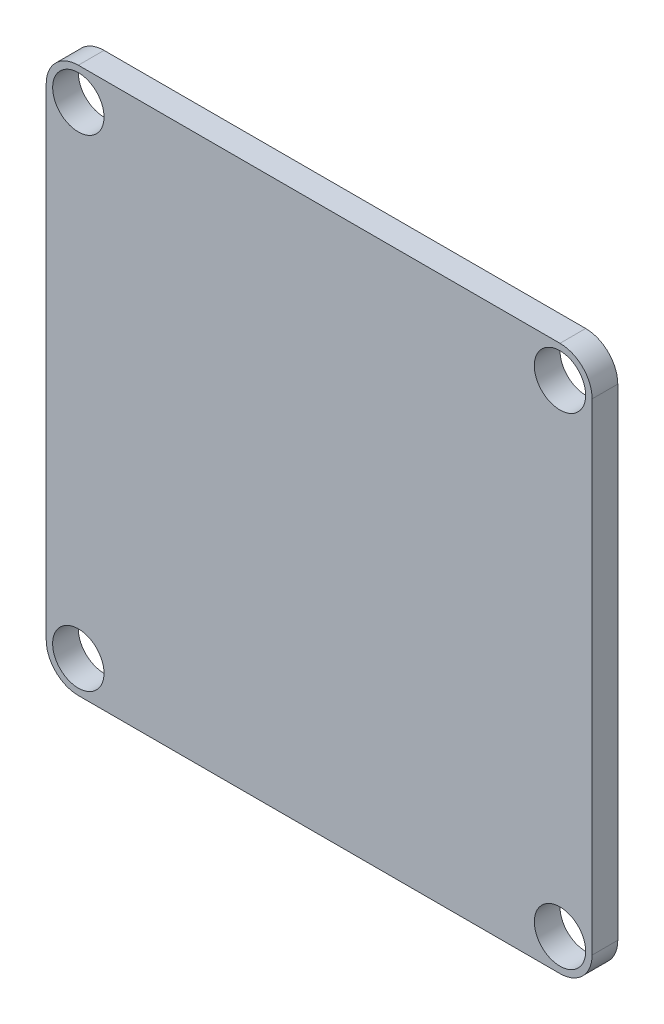
SolidWorks part; units mm, degrees
ref_plane "Front Plane" through (0, 0, 0) normal (0, 0, 1) x (1, 0, 0)
ref_plane "Top Plane" through (0, 0, 0) normal (0, 1, 0) x (1, 0, 0)
ref_plane "Right Plane" through (0, 0, 0) normal (1, 0, 0) x (0, 0, -1)
sketch "Sketch1" plane through (0, 0, 0) normal (0, 0, 1) x (1, 0, 0)
  line L0 (1.7643, 13.6116) -> (1.7643, -20.3884) construction
  line L1 (-13.2357, 13.6116) -> (16.7643, 13.6116)
  line L2 (-15.2357, 11.6116) -> (-15.2357, -18.3884)
  line L3 (-13.2357, -20.3884) -> (16.7643, -20.3884)
  line L4 (18.7643, 11.6116) -> (18.7643, -18.3884)
  line L5 (-15.2357, -3.3884) -> (18.7643, -3.3884) construction
  circle A0 centre (16.7643, 11.6116) radius 1.6
  arc A1 (-13.2357, 13.6116) -> (-15.2357, 11.6116) centre (-13.2357, 11.6116) ccw
  arc A2 (-15.2357, -18.3884) -> (-13.2357, -20.3884) centre (-13.2357, -18.3884) ccw
  arc A3 (16.7643, -20.3884) -> (18.7643, -18.3884) centre (16.7643, -18.3884) ccw
  arc A4 (16.7643, 13.6116) -> (18.7643, 11.6116) centre (16.7643, 11.6116) cw
  circle A5 centre (16.7643, -18.3884) radius 1.6
  circle A6 centre (-13.2357, 11.6116) radius 1.6
  circle A7 centre (-13.2357, -18.3884) radius 1.6
  point P12 (-15.2357, 13.6116)
  point P17 (18.7643, -20.3884)
  point P20 (18.7643, 13.6116)
  dimension "D3" = 2
extrude "Boss-Extrude1" add sketch "Sketch1" along normal blind 1.6
